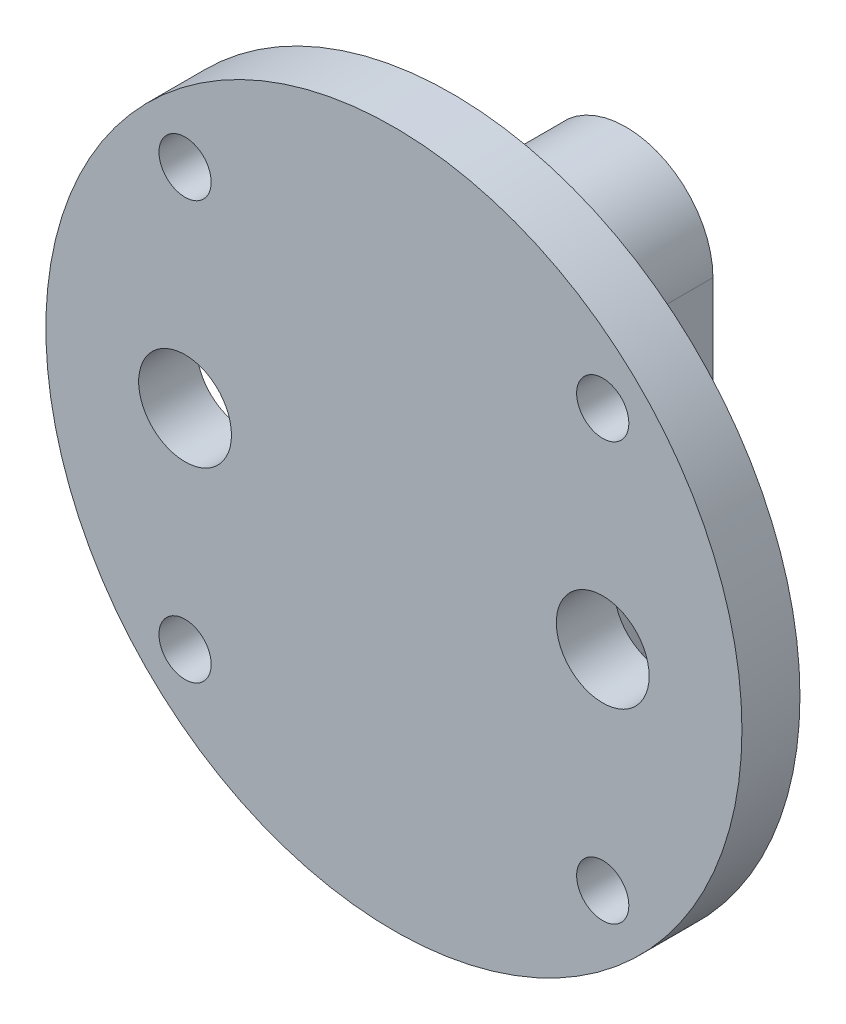
SolidWorks part; units mm, degrees
ref_plane "Plan de face" through (0, 0, 0) normal (0, 0, 1) x (1, 0, 0)
ref_plane "Plan de dessus" through (0, 0, 0) normal (0, 1, 0) x (1, 0, 0)
ref_plane "Plan de droite" through (0, 0, 0) normal (1, 0, 0) x (0, 0, -1)
sketch "Esquisse1" plane through (0, 0, 0) normal (0, 0, 1) x (1, 0, 0)
  line L0 (18, 0) -> (-18, 0) construction
  line L1 (18, 18) -> (-18, 18) construction
  line L2 (18, 18) -> (18, -18) construction
  line L3 (18, -18) -> (-18, -18) construction
  line L4 (-18, 18) -> (-18, -18) construction
  line L5 (18, 18) -> (-18, -18) construction
  line L6 (18, -18) -> (-18, 18) construction
  circle A0 centre (0, 0) radius 30
  circle A2 centre (18, 18) radius 2.25
  circle A3 centre (-18, 18) radius 2.25
  circle A4 centre (-18, -18) radius 2.25
  circle A5 centre (18, -18) radius 2.25
  circle A8 centre (18, 0) radius 4
  circle A9 centre (-18, 0) radius 4
  point P14 (0, 0)
  dimension "D1" = 60
  dimension "D2" = 8
  dimension "D3" = 4.5
  dimension "D4" = 36
  dimension "D5" = 36
extrude "Boss.-Extru.1" add sketch "Esquisse1" along normal blind 5
sketch "Esquisse2" plane through (0, 0, 0) normal (0, 0, -1) x (-1, 0, 0)
  line L0 (0, 12.5) -> (0, -12.5) construction
  line L3 (7.5, 12.5) -> (7.5, -12.5)
  line L4 (-7.5, 12.5) -> (-7.5, -12.5)
  arc A4 (7.5, 12.5) -> (-7.5, 12.5) centre (0, 12.5) ccw
  arc A5 (-7.5, -12.5) -> (7.5, -12.5) centre (0, -12.5) ccw
  circle A6 centre (0, 12.5) radius 2.8
  circle A7 centre (0, -12.5) radius 2.8
  point P3 (0, 0)
  dimension "D1" = 15
  dimension "D2" = 25
  dimension "D3" = 5.6
extrude "Boss.-Extru.2" add sketch "Esquisse2" along normal blind 15
